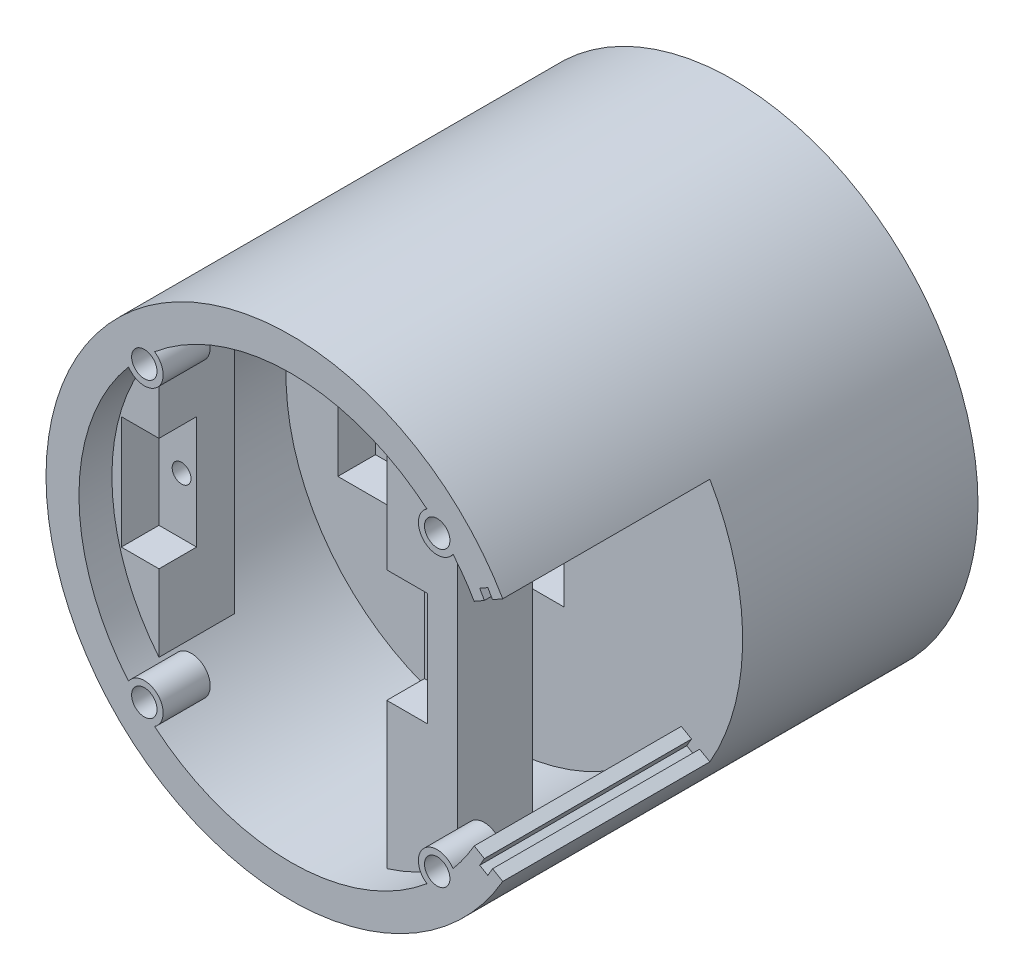
SolidWorks part; units mm, degrees
ref_plane "Спереди" through (0, 0, 0) normal (0, 0, 1) x (1, 0, 0)
ref_plane "Сверху" through (0, 0, 0) normal (0, 1, 0) x (1, 0, 0)
ref_plane "Справа" through (0, 0, 0) normal (1, 0, 0) x (0, 0, -1)
sketch "Эскиз1" plane through (0, 0, 0) normal (0, 0, 1) x (1, 0, 0)
  circle A1 centre (0, 0) radius 26
  dimension "D1" = 52
extrude "Бобышка-Вытянуть1" add sketch "Эскиз1" along normal blind 47
sketch "Эскиз3" plane through (0, 0, 0) normal (0, 0, -1) x (-1, 0, 0)
  circle A0 centre (0, 0) radius 22.5
  dimension "D1" = 45
extrude "Вырез-Вытянуть1" cut sketch "Эскиз3" against normal blind 20 contours A0
sketch "Эскиз10" plane through (0, 0, 20) normal (0, 0, -1) x (-1, 0, 0)
  circle A0 centre (0, 0) radius 15
  dimension "D1" = 30
sketch "Эскиз4" plane through (0, 0, 47) normal (0, 0, 1) x (1, 0, 0)
  circle A0 centre (0, 0) radius 22.5
  dimension "D1" = 45
extrude "Вырез-Вытянуть2" cut sketch "Эскиз4" against normal offset from surface (22 mm away) 5 up to face at (-22.5, 0, 20)
sketch "Эскиз13" plane through (0, 0, 25) normal (0, 0, 1) x (1, 0, 0)
  line L0 (0, 26) -> (0, -26) construction
  line L1 (-26, 0) -> (26, 0) construction
  line L3 (-17, 6.5) -> (7, 6.5)
  line L4 (-17, 6.5) -> (-17, -6.5)
  line L5 (-17, -6.5) -> (7, -6.5)
  line L6 (7, 6.5) -> (7, -6.5)
  circle A0 centre (0, 0) radius 26 construction
  point P11 (-17, 0)
  point P13 (-5, 6.5)
  dimension "D1" = 13
  dimension "D2" = 24
  dimension "D3" = 5
extrude "Вырез-Вытянуть3" cut sketch "Эскиз13" against normal blind 4
sketch "Эскиз12" plane through (0, 0, 47) normal (0, 0, 1) x (1, 0, 0)
  line L0 (0, 26) -> (0, -26) construction
  line L1 (0, 0) -> (28.1458, 16.25) construction
  line L2 (-26, 0) -> (32.5, 0) construction
  line L5 (19.4856, 11.25) -> (22.5167, 13)
  line L6 (19.4856, -11.25) -> (22.5167, -13)
  circle A0 centre (0, 0) radius 26 construction
  arc A4 (19.4856, -11.25) -> (19.4856, 11.25) centre (0, 0) ccw
  arc A6 (22.5167, -13) -> (22.5167, 13) centre (0, 0) ccw
  dimension "D1" = 30
extrude "Вырез-Вытянуть4" cut sketch "Эскиз12" along direction (0, 0, -1) on the side against the normal up to surface (22 mm away)
ref_plane "Плоскость2" through (0, 0, 35.5) normal (0, 0, 1) x (1, 0, 0)
sketch "Эскиз14" plane through (0, 0, 35.5) normal (0, 0, 1) x (1, 0, 0)
  line L1 (7, 0) -> (-46.5151, 0) construction
  line L2 (7, -6.5) -> (7, 6.5) construction
  line L3 (-17.5, -28.5313) -> (-17.5, 17.8536) construction
  line L6 (7, 0) -> (57.6607, 0) construction
  line L8 (14.2, -44.5711) -> (14.2, 20) construction
  line L10 (14.2, -20.5757) -> (14.2, 20.5757)
  line L13 (-17.5, -17.8536) -> (-17.5, 17.8536)
  line L15 (6.7, -24.0855) -> (6.7, 24.0855)
  line L16 (0, -28.5313) -> (0, 28.5313) construction
  arc A4 (-17.5, 17.8536) -> (-17.5, -17.8536) centre (0, 0) ccw
  arc A5 (14.2, 20.5757) -> (6.7, 24.0855) centre (0, 0) ccw
  arc A6 (6.7, -24.0855) -> (14.2, -20.5757) centre (0, 0) ccw
  point P11 (-17.5, 0)
  point P18 (7, 0)
  point P22 (14.2, 0)
  point P27 (14.2, 0)
  point P29 (-17.5, 0)
  point P33 (7.5, 0)
  point P34 (6.7, 0)
  point P35 (0, 0)
  dimension "D1" = 17.5
  dimension "D4" = 6.7
extrude "Бобышка-Вытянуть2" add sketch "Эскиз14" along normal blind 8
sketch "Эскиз15" plane through (0, 0, 43.5) normal (0, 0, 1) x (1, 0, 0)
  line L0 (43.3889, 0) -> (-43.3889, 0) construction
  line L1 (0, 36.1435) -> (0, -36.1435) construction
  line L2 (-21.5, 29.8665) -> (-21.5, -29.8665) construction
  line L3 (11, 32.0712) -> (11, -32.0712) construction
  line L4 (-17.5, 23.7559) -> (-17.5, -23.2484) construction
  line L5 (-21.5, -6) -> (-21.5, 6)
  line L6 (-21.5, 6) -> (-17.5, 6)
  line L7 (6.7, 41.39) -> (6.7, -19.4927) construction
  line L8 (6.7, 21.4793) -> (6.7, -21.4793) construction
  line L9 (11, -6) -> (11, 6)
  line L10 (11, 6) -> (6.7, 6)
  line L11 (-17.5, 6) -> (-17.5, -6)
  line L12 (6.7, 6) -> (6.7, -6)
  line L13 (11, -6) -> (6.7, -6)
  line L14 (-21.5, -6) -> (-17.5, -6)
  point P4 (0, 0)
  point P8 (0, 0)
  point P11 (-21.5, 0)
  point P14 (11, 0)
  point P19 (-17.5, 0.2537)
  point P24 (6.7, 10.9487)
  point P30 (6.7, 0)
  point P31 (11, 0)
  point P32 (-17.5, 0)
  point P33 (-21.5, 0)
  dimension "D1" = 21.5
  dimension "D2" = 11
  dimension "D3" = 6
  dimension "D4" = 6
extrude "Вырез-Вытянуть5" cut sketch "Эскиз15" along direction (0, 0, 1) on the side against the normal offset from surface (4 mm away) 18.5
sketch "Эскиз17" plane through (0, 0, 39.5) normal (0, 0, 1) x (1, 0, 0)
  circle A1 centre (-19.1, 0) radius 1
  circle A2 centre (8.6, 0) radius 1
extrude "Вырез-Вытянуть6" cut sketch "Эскиз17" along direction (0, 0, 1) on the side against the normal up to surface (4 mm away)
chamfer "Фаска1" distance 1 angle 45 1 edges at (-22.5, 0, 0)
sketch "Эскиз20" plane through (0, 0, 47) normal (0, 0, 1) x (1, 0, 0)
  line L0 (-57.2124, 0) -> (57.2124, 0) construction
  line L1 (0, 34.3681) -> (0, -34.3681) construction
  line L2 (0, 0) -> (-44.2288, 44.2288) construction
  circle A0 centre (0, 0) radius 22 construction
  circle A2 centre (0, 0) radius 26 construction
  circle A3 centre (-15.5563, 15.5563) radius 2
  circle A4 centre (15.5563, 15.5563) radius 2
  circle A5 centre (15.5563, -15.5563) radius 2
  circle A6 centre (-15.5563, -15.5563) radius 2
  point P3 (-15.5563, 15.5563)
  point P8 (0, 0)
  point P12 (0, 0)
  point P23 (0, 0)
  point P27 (0, 0)
  dimension "D2" = 52
  dimension "D3" = 22
  dimension "D1" = 4
  dimension "D4" = 4
extrude "Бобышка-Вытянуть3" add sketch "Эскиз20" against normal blind 5
sketch "Эскиз21" plane through (0, 0, 47) normal (0, 0, 1) x (1, 0, 0)
  circle A4 centre (-15.5563, 15.5563) radius 1.35
  circle A5 centre (15.5563, 15.5563) radius 1.35
  circle A6 centre (15.5563, -15.5563) radius 1.35
  circle A7 centre (-15.5563, -15.5563) radius 1.35
  point P12 (0, 0)
  point P14 (0, 0)
  dimension "D1" = 2.7
  dimension "D2" = 4
extrude "Вырез-Вытянуть9" cut sketch "Эскиз21" against normal blind 5
sketch "Эскиз22" plane through (0, 0, 0) normal (0.5, -0.866, 0) x (0.866, 0.5, 0)
  line L0 (24.25, 47) -> (24.25, 25) construction
  line L1 (22.5, 47) -> (26, 47) construction
  line L2 (22.5, 25) -> (26, 25) construction
  line L3 (24.75, 47) -> (23.75, 47)
  line L4 (23.75, 47) -> (23.75, 25)
  line L5 (26, 25) -> (13, 25) construction
  line L6 (23.75, 25) -> (24.75, 25)
  line L7 (24.75, 47) -> (24.75, 25)
  dimension "D1" = 0.5
extrude "Вырез-Вытянуть10" cut sketch "Эскиз22" against normal blind 1
sketch "Эскиз23" plane through (0, 0, 0) normal (0.5, 0.866, 0) x (0.866, -0.5, 0)
  line L0 (24.25, -25) -> (24.25, -47) construction
  line L1 (22.5, -25) -> (26, -25) construction
  line L2 (22.5, -47) -> (26, -47) construction
  line L3 (24.75, -25) -> (23.75, -25)
  line L4 (23.75, -25) -> (23.75, -47)
  line L5 (23.75, -47) -> (24.75, -47)
  line L6 (24.75, -25) -> (24.75, -47)
  dimension "D1" = 0.5
extrude "Вырез-Вытянуть11" cut sketch "Эскиз23" against normal blind 1
